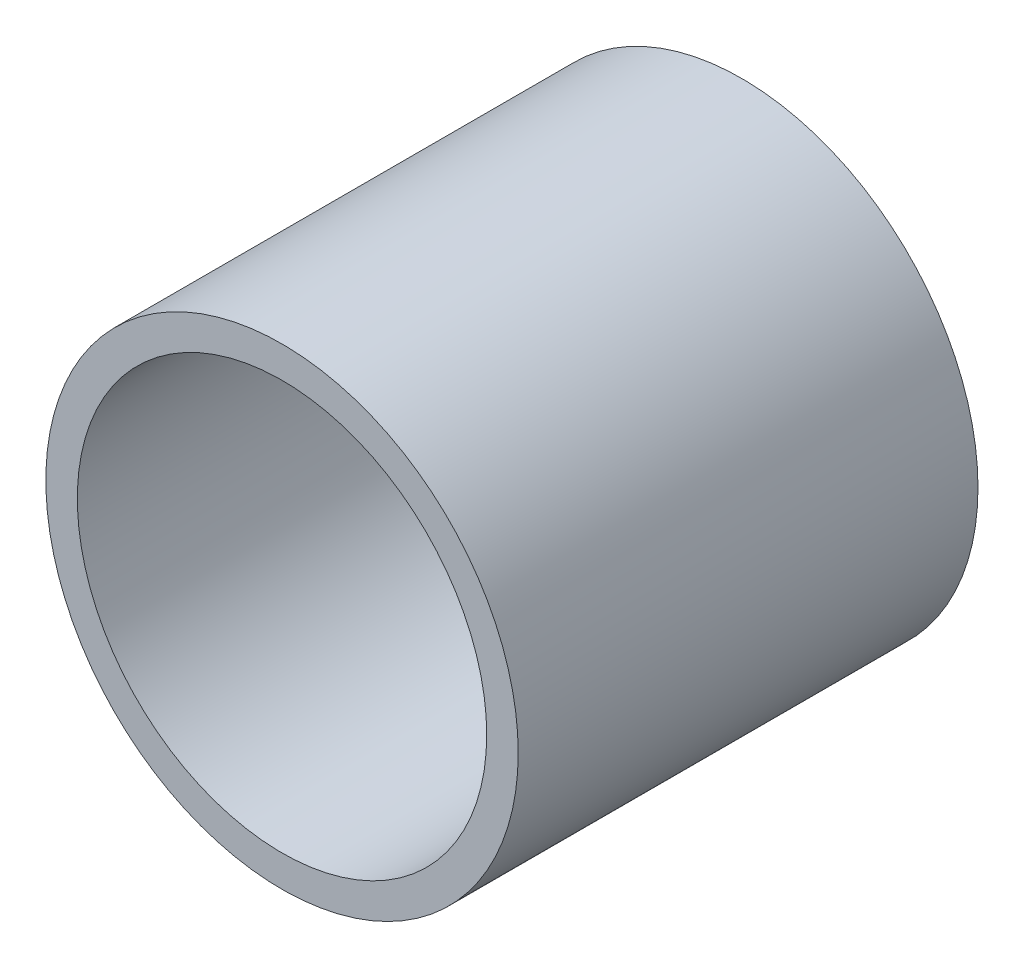
SolidWorks part; units mm, degrees
material "ABS"
ref_plane "正面" through (0, 0, 0) normal (0, 0, 1) x (1, 0, 0)
ref_plane "平面" through (0, 0, 0) normal (0, 1, 0) x (1, 0, 0)
ref_plane "右側面" through (0, 0, 0) normal (1, 0, 0) x (0, 0, -1)
sketch "ｽｹｯﾁ1" plane through (0, 0, 0) normal (0, 0, 1) x (1, 0, 0)
  circle A0 centre (0, 0) radius 3.75
  circle A1 centre (0, 0) radius 3.25
  dimension "D1" = 6.5
  dimension "D2" = 7.5
extrude "ﾎﾞｽ - 押し出し1" add sketch "ｽｹｯﾁ1" along normal blind 7.3
